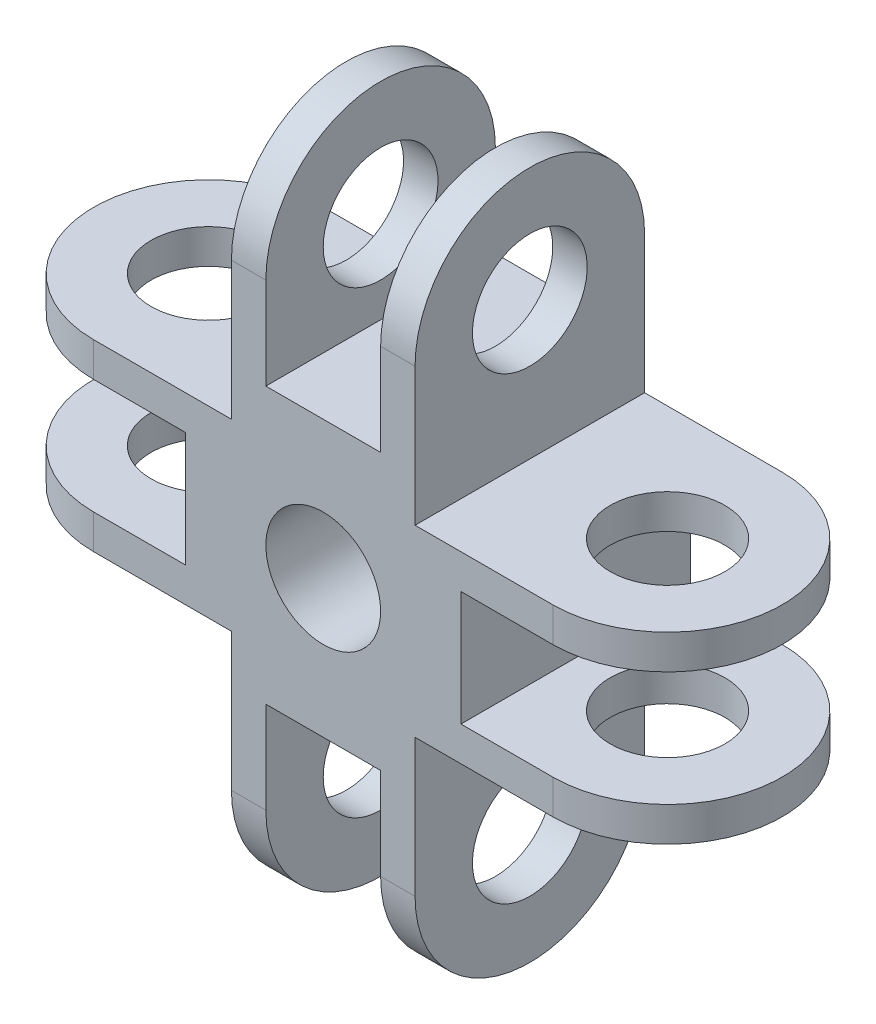
SolidWorks part; units mm, degrees
ref_plane "前视基准面" through (0, 0, 0) normal (0, 0, 1) x (1, 0, 0)
ref_plane "上视基准面" through (0, 0, 0) normal (0, 1, 0) x (1, 0, 0)
ref_plane "右视基准面" through (0, 0, 0) normal (1, 0, 0) x (0, 0, -1)
sketch "草图1" plane through (0, 0, 0) normal (0, 0, 1) x (1, 0, 0)
  circle A0 centre (0, 0) radius 5
  circle A1 centre (0, 0) radius 2.5
  dimension "D1" = 10
  dimension "D2" = 5
extrude "凸台-拉伸1" add sketch "草图1" along normal blind 10
sketch "草图2" plane through (0, 0, 0) normal (0, 1, 0) x (1, 0, 0)
  line L0 (-5, 0) -> (-10, 0)
  line L1 (-5, -10) -> (-10, -10)
  line L2 (-5, 0) -> (-4.6327, 0)
  line L3 (5, 0) -> (-5, 0) construction
  line L5 (-5, -10) -> (5, -10) construction
  line L6 (-4.6327, -10) -> (-5, -10)
  line L7 (-4.6327, 0) -> (-3.9732, 0)
  line L8 (-3.9732, 0) -> (-3.9732, -10)
  line L9 (-3.9732, -10) -> (-4.6327, -10)
  arc A0 (-10, 0) -> (-10, -10) centre (-10, -5) ccw
  circle A1 centre (-10, -5) radius 2.5
  dimension "D1" = 5
extrude "凸台-拉伸2" add sketch "草图2" along normal mid plane 8
pattern_circular "阵列(圆周)1" count 4 every 90 about axis through (0, 0, 0) along (0, 0, 1) of "凸台-拉伸2"
sketch "草图4" plane through (0, 0, 0) normal (0, 1, 0) x (1, 0, 0)
  line L0 (-10, 0) -> (-6, 0)
  line L1 (-4, 0) -> (-10, 0) construction
  line L2 (-6, 0) -> (-6, -10)
  line L3 (-10, -10) -> (-4, -10) construction
  line L4 (-6, -10) -> (-10, -10)
  arc A0 (-10, 0) -> (-10, -10) centre (-10, -5) ccw
extrude "切除-拉伸2" cut sketch "草图4" against normal mid plane 5
pattern_circular "阵列(圆周)2" count 4 every 90 about axis through (0, 0, 0) along (0, 0, 1) of "切除-拉伸2"
sketch "草图5" plane through (0, 0, 0) normal (0, 0, -1) x (-1, 0, 0)
  line L0 (-3.9732, 3.9732) -> (-3.0355, 3.9732)
  line L1 (-3.0355, 3.9732) -> (-3.9732, 3.0355)
  line L2 (-3.9732, 3.0355) -> (-3.9732, 3.9732)
extrude "凸台-拉伸5" add sketch "草图5" against normal blind 10
pattern_circular "阵列(圆周)3" count 4 every 90 of "凸台-拉伸5"
